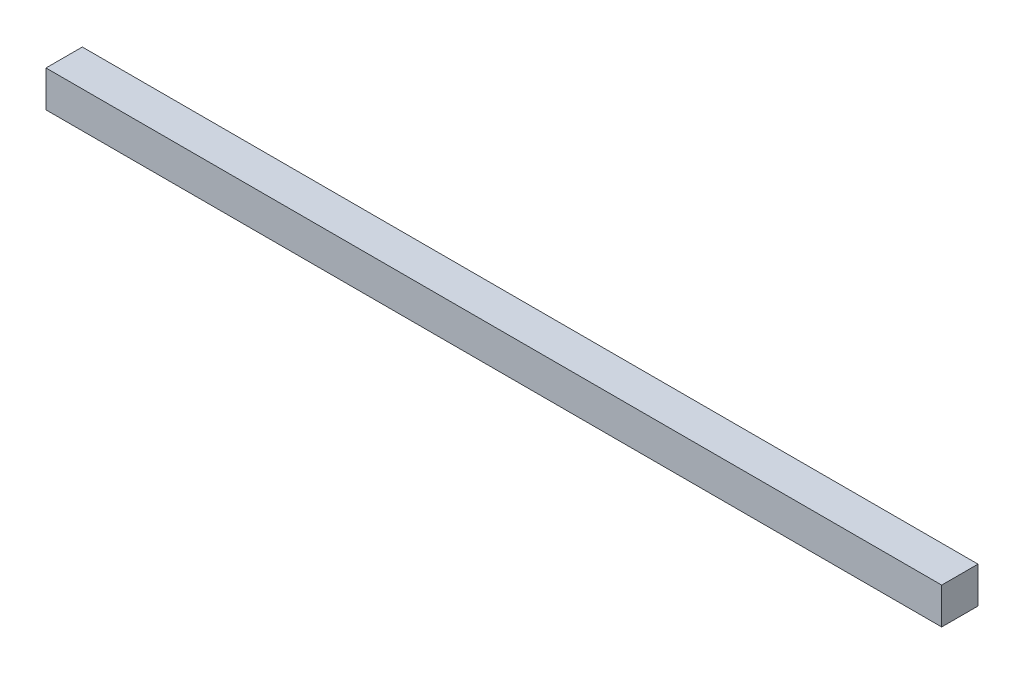
SolidWorks part; units mm, degrees
ref_plane "前视基准面" through (0, 0, 0) normal (0, 0, 1) x (1, 0, 0)
ref_plane "上视基准面" through (0, 0, 0) normal (0, 1, 0) x (1, 0, 0)
ref_plane "右视基准面" through (0, 0, 0) normal (1, 0, 0) x (0, 0, -1)
sketch "草图1" plane through (0, 0, 0) normal (0, 1, 0) x (1, 0, 0)
  line L1 (-185, 7.5) -> (185, 7.5)
  line L2 (-185, 7.5) -> (-185, -7.5)
  line L3 (-185, -7.5) -> (185, -7.5)
  line L4 (185, 7.5) -> (185, -7.5)
  line L5 (-185, 7.5) -> (185, -7.5) construction
  line L6 (-185, -7.5) -> (185, 7.5) construction
  point P0 (0, 0)
  dimension "D1" = 370
  dimension "D2" = 15
extrude "凸台-拉伸1" add sketch "草图1" along normal blind 15
